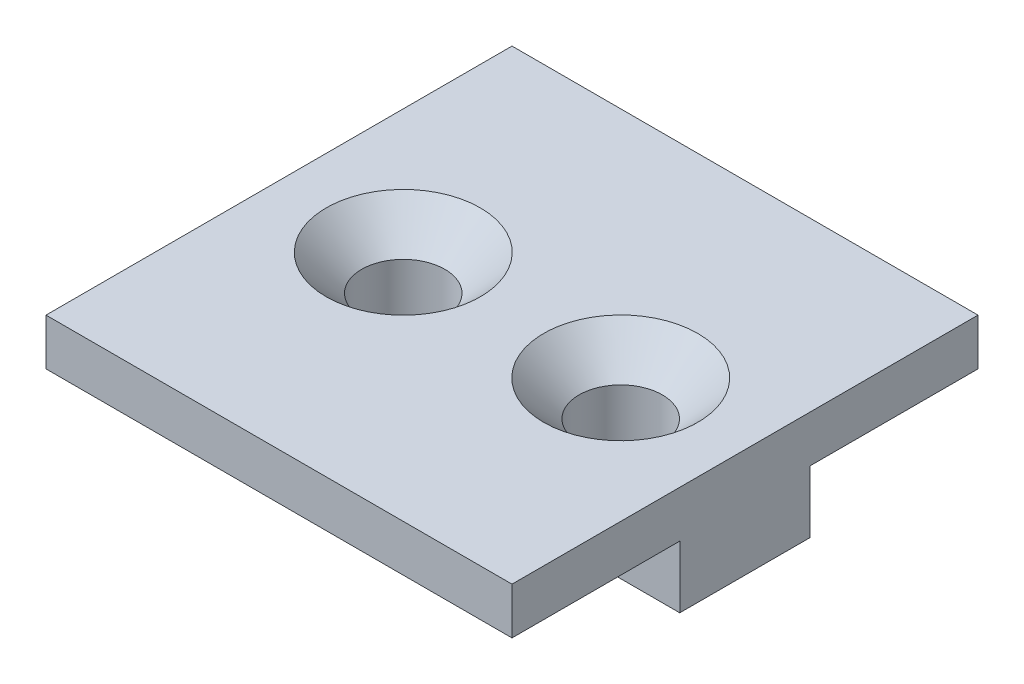
SolidWorks part; units mm, degrees
ref_plane "Front Plane" through (0, 0, 0) normal (0, 0, 1) x (1, 0, 0)
ref_plane "Top Plane" through (0, 0, 0) normal (0, 1, 0) x (1, 0, 0)
ref_plane "Right Plane" through (0, 0, 0) normal (1, 0, 0) x (0, 0, -1)
sketch "Sketch1" plane through (0, 0, 0) normal (0, 1, 0) x (1, 0, 0)
  line L1 (9.525, 2.667) -> (-9.525, 2.667)
  line L2 (9.525, 2.667) -> (9.525, -2.667)
  line L3 (9.525, -2.667) -> (-9.525, -2.667)
  line L4 (-9.525, 2.667) -> (-9.525, -2.667)
  line L5 (9.525, 2.667) -> (-9.525, -2.667) construction
  line L6 (9.525, -2.667) -> (-9.525, 2.667) construction
  point P0 (0, 0)
  dimension "D1" = 5.334
  dimension "D2" = 19.05
extrude "Boss-Extrude1" add sketch "Sketch1" along normal blind 2.54
sketch "Sketch2" plane through (0, 2.54, 0) normal (0, 1, 0) x (1, 0, 0)
  line L0 (-9.525, 2.667) -> (-9.525, -2.667) construction
  line L1 (9.525, 9.525) -> (-9.525, 9.525)
  line L2 (9.525, 9.525) -> (9.525, -9.525)
  line L3 (9.525, -9.525) -> (-9.525, -9.525)
  line L4 (-9.525, 9.525) -> (-9.525, -9.525)
  line L5 (9.525, 9.525) -> (-9.525, -9.525) construction
  line L6 (9.525, -9.525) -> (-9.525, 9.525) construction
  point P0 (0, 0)
  dimension "D1" = 19.05
extrude "Boss-Extrude2" add sketch "Sketch2" along normal blind 1.905
sketch "Sketch3" plane through (0, 4.445, 0) normal (0, 1, 0) x (1, 0, 0)
  line L0 (-4.445, 0) -> (4.445, 0) construction
  point P3 (0, 0)
  dimension "D1" = 8.89
hole_wizard "CSK for M3 Flat Head Machine Screw1" positions "Sketch4" profile "Sketch5" countersink size "M3" standard "ANSI Metric" end condition through all
sketch "Sketch4" plane through (0, 4.445, 0) normal (0, 1, 0) x (1, 0, 0)
  point P0 (-4.445, 0)
  point P3 (4.445, 0)
sketch "Sketch5" plane through (-4.445, 4.445, 0) normal (1, 0, 0) x (0, 0, 1)
  line L0 (0, 0) -> (0, 4.445)
  line L1 (0, 4.445) -> (1.7, 4.445)
  line L2 (1.7, 4.445) -> (1.7, 1.45)
  line L3 (1.7, 1.45) -> (3.15, 0)
  line L5 (3.15, 0) -> (0, 0)
  line L6 (-1.7, 1.45) -> (-3.15, 0) construction
  line L11 (0, -6.35) -> (0, 107.95) construction
  dimension "Thru Hole Dia." = 3.4
  dimension "Thru Hole Depth" = 4.445
  dimension "Near C'Sink Dia." = 6.3
  dimension "Near C'Sink Angle" = 90
